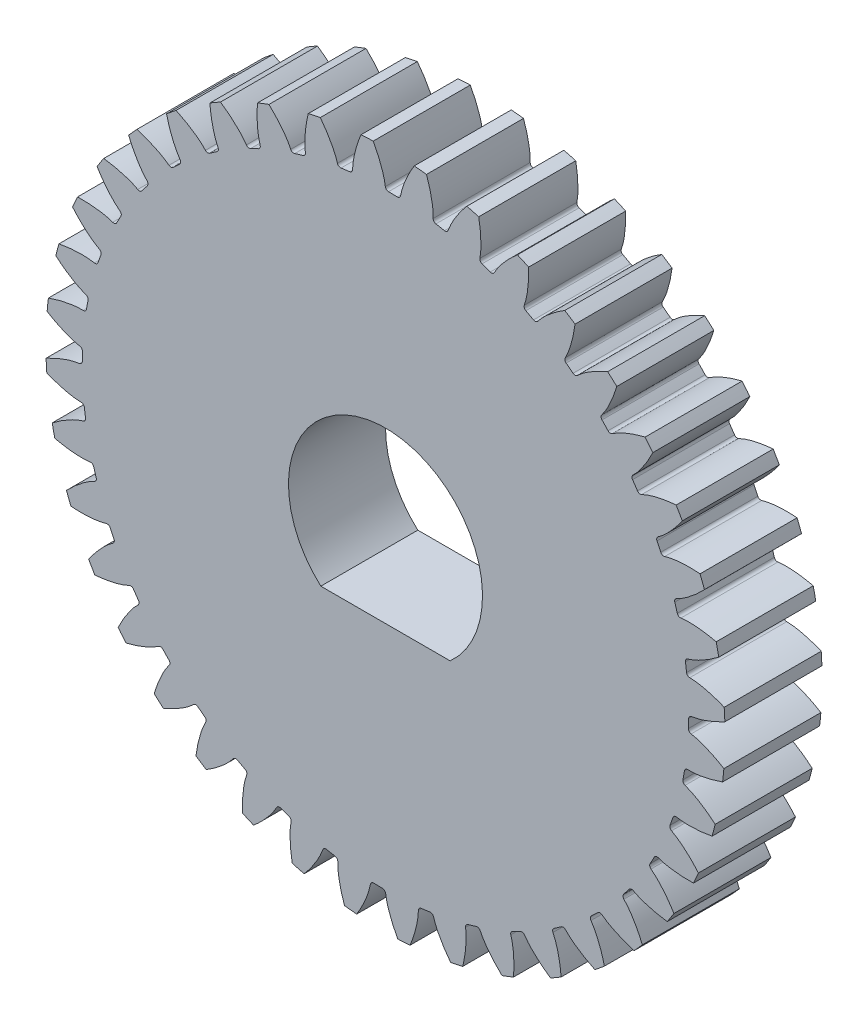
SolidWorks part; units mm, degrees
ref_plane "Front Plane" through (0, 0, 0) normal (0, 0, 1) x (1, 0, 0)
ref_plane "Top Plane" through (0, 0, 0) normal (0, 1, 0) x (1, 0, 0)
ref_plane "Right Plane" through (0, 0, 0) normal (1, 0, 0) x (0, 0, -1)
sketch "Sketch1" plane through (0, 0, 0) normal (0, 0, 1) x (1, 0, 0)
  line L0 (-2, -2.2361) -> (2, -2.2361)
  circle A0 centre (0, 0) radius 10.5
  arc A1 (2, -2.2361) -> (-2, -2.2361) centre (0, 0) ccw
  dimension "D1" = 21
  dimension "D2" = 6
  dimension "D3" = 4
extrude "Boss-Extrude1" add sketch "Sketch1" along normal blind 3
sketch "Sketch3" plane through (0, 0, 0) normal (0, 0, 1) x (1, 0, 0)
  line L0 (9.375, 0) -> (9.3969, 0)
  line L2 (9.3639, -0.4567) -> (9.3858, -0.4577)
  line L3 (0, 0) -> (10.4969, -0.2558) construction
  circle A0 centre (0, 0) radius 10 construction
  circle A1 centre (0, 0) radius 9.3969 construction
  arc A2 (9.3639, -0.4567) -> (9.375, 0) centre (0, 0) ccw
  circle A3 centre (0, 0) radius 10.5 construction
  spline S0 degree 4 poles (9.3969, 0) (9.4001, 0) (9.4091, 0.0003) (9.4262, 0.0014) (9.4539, 0.004) (9.4892, 0.0084) (9.5346, 0.0155) (9.588, 0.0256) (9.6465, 0.0385) (9.7099, 0.0545) (9.7728, 0.0722) (9.8354, 0.0914) (9.8974, 0.112) (9.9723, 0.1386) (10.0615, 0.1728) (10.1651, 0.2163) (10.2816, 0.2695) (10.3992, 0.328) (10.514, 0.389) (10.6287, 0.4546) (10.7389, 0.5208) (10.852, 0.5936) (10.9558, 0.6628) (11.0704, 0.7447) (11.1625, 0.8121) (11.2821, 0.9055) (11.3523, 0.9621) (11.4337, 1.0298) (11.4695, 1.0607) (11.4916, 1.0797) knots 0 0 0 0 0 0.005377 0.015084 0.028532 0.04661 0.064855 0.092111 0.119476 0.146842 0.174209 0.201575 0.228941 0.256307 0.307035 0.361767 0.4165 0.471232 0.525964 0.580697 0.635429 0.690161 0.744894 0.799626 0.854358 0.909091 0.954545 1 1 1 1 1 construction
  spline S1 degree 4 poles (9.3969, 0) (9.4001, 0) (9.4091, 0.0003) (9.4262, 0.0014) (9.4539, 0.004) (9.4892, 0.0084) (9.5346, 0.0155) (9.588, 0.0256) (9.6465, 0.0385) (9.7099, 0.0545) (9.7728, 0.0722) (9.8354, 0.0914) (9.8974, 0.112) (9.9723, 0.1386) (10.0615, 0.1728) (10.1651, 0.2163) (10.2816, 0.2695) (10.3992, 0.328) (10.514, 0.389) (10.6287, 0.4546) (10.7389, 0.5208) (10.852, 0.5936) (10.9558, 0.6628) (11.0704, 0.7447) (11.1625, 0.8121) (11.2562, 0.8853) (11.3016, 0.9214) (11.3247, 0.9401) knots 0 0 0 0 0 0.005377 0.015084 0.028532 0.04661 0.064855 0.092111 0.119476 0.146842 0.174209 0.201575 0.228941 0.256307 0.307035 0.361767 0.4165 0.471232 0.525964 0.580697 0.635429 0.690161 0.744894 0.799626 0.854358 0.909091 0.909091 0.909091 0.909091 0.909091
  spline S2 degree 4 poles (9.3858, -0.4577) (9.389, -0.4579) (9.398, -0.4587) (9.4149, -0.4606) (9.4425, -0.4645) (9.4775, -0.4706) (9.5226, -0.4799) (9.5754, -0.4926) (9.6332, -0.5084) (9.6957, -0.5274) (9.7577, -0.5481) (9.8193, -0.5704) (9.8802, -0.5939) (9.9537, -0.6242) (10.0412, -0.6627) (10.1425, -0.7112) (10.2562, -0.77) (10.3709, -0.8342) (10.4825, -0.9007) (10.594, -0.9718) (10.7008, -1.0433) (10.8102, -1.1215) (10.9105, -1.1957) (11.021, -1.2831) (11.1097, -1.3549) (11.2246, -1.454) (11.2919, -1.5139) (11.37, -1.5855) (11.4043, -1.6182) (11.4254, -1.6382) knots 0 0 0 0 0 0.005377 0.015084 0.028532 0.04661 0.064855 0.092111 0.119476 0.146842 0.174209 0.201575 0.228941 0.256307 0.307035 0.361767 0.4165 0.471232 0.525964 0.580697 0.635429 0.690161 0.744894 0.799626 0.854358 0.909091 0.954545 1 1 1 1 1 construction
  spline S3 degree 4 poles (9.3858, -0.4577) (9.389, -0.4579) (9.398, -0.4587) (9.4149, -0.4606) (9.4425, -0.4645) (9.4775, -0.4706) (9.5226, -0.4799) (9.5754, -0.4926) (9.6332, -0.5084) (9.6957, -0.5274) (9.7577, -0.5481) (9.8193, -0.5704) (9.8802, -0.5939) (9.9537, -0.6242) (10.0412, -0.6627) (10.1425, -0.7112) (10.2562, -0.77) (10.3709, -0.8342) (10.4825, -0.9007) (10.594, -0.9718) (10.7008, -1.0433) (10.8102, -1.1215) (10.9105, -1.1957) (11.021, -1.2831) (11.1097, -1.3549) (11.1997, -1.4325) (11.2433, -1.4708) (11.2655, -1.4906) knots 0 0 0 0 0 0.005377 0.015084 0.028532 0.04661 0.064855 0.092111 0.119476 0.146842 0.174209 0.201575 0.228941 0.256307 0.307035 0.361767 0.4165 0.471232 0.525964 0.580697 0.635429 0.690161 0.744894 0.799626 0.854358 0.909091 0.909091 0.909091 0.909091 0.909091
  point P5 (9.375, 0)
  point P11 (9.3639, -0.4567)
  dimension "D1" = 20
  dimension "D2" = 18.7939
  dimension "D3" = 18.75
  dimension "D4" = 1.396
  dimension "D5" = 1.396
extrude "Cut-Extrude1" cut sketch "Sketch3" against normal through all and the other way through all
fillet "Fillet1" radius 0.1 1 edges at (9.3639, -0.4567, 1.5)
fillet "Fillet2" radius 0.1 1 edges at (9.375, 0, 1.5)
pattern_circular "CirPattern14" count 40 over 360 about axis through (0, 0, 3) along (0, 0, -1) of "Cut-Extrude1", "Fillet1", "Fillet2"
equation "\"P\"= 2'Diametral Pitch"
equation "\"N\"= 40'Number of teeth"
equation "\"phi\"= 20deg'pressure angle"
equation "\"a\"= 1 / \"P\"'addendum"
equation "\"b\"= 1.25 / \"P\"'dedendum"
equation "\"c\"= \"b\" - \"a\"'clearance"
equation "\"dp\"= \"N\" / \"P\"'pitch circle diameter"
equation "\"db\"= \"dp\" * cos ( \"phi\" )'base circle diameter"
equation "\"D1@Sketch1\"= \"dp\" + 2 * \"a\"'Addendum circle diameter"
equation "\"D1@Sketch3\"= \"dp\"'pitch circle"
equation "\"D2@Sketch3\"= \"db\" 'base circle"
equation "\"D3@Sketch3\" = \"dp\" - 2 * \"b\"'dedendum circle"
equation "\"alpha\"= sqr ( \"dp\" ^ 2 - \"db\" ^ 2 ) / \"db\" * 180 / pi - \"phi\"'alpha (deg)"
equation "\"beta\"= ( 360 / ( 4 * \"N\" ) - \"alpha\" ) * 2"
equation "\"D4@Sketch3\"= 360 / ( 4 * \"N\" ) - \"alpha\""
equation "\"D5@Sketch3\"= 360 / ( 4 * \"N\" ) - \"alpha\""
